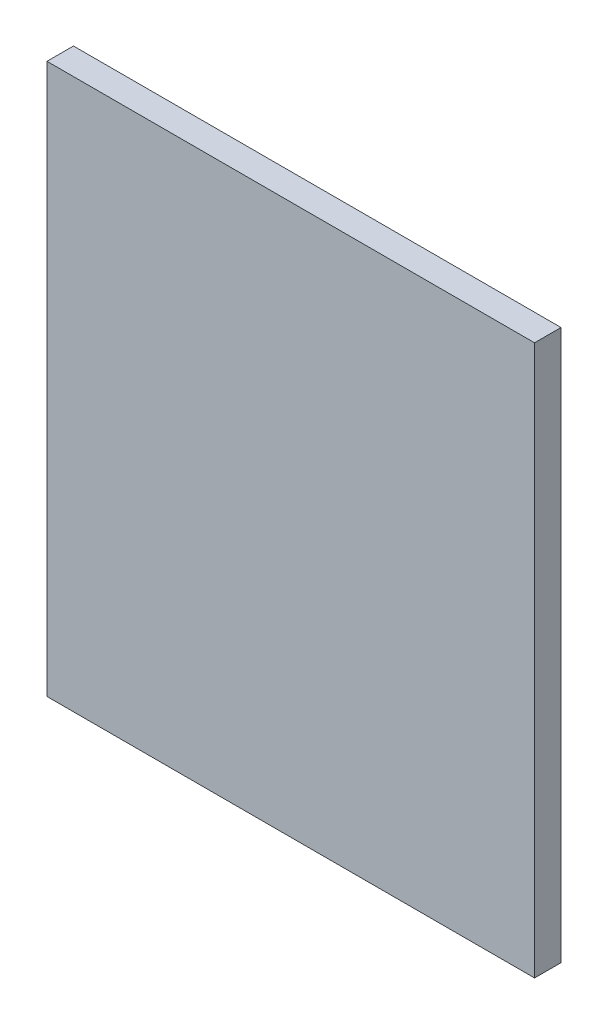
SolidWorks part; units mm, degrees
ref_plane "Alzado" through (0, 0, 0) normal (0, 0, 1) x (1, 0, 0)
ref_plane "Planta" through (0, 0, 0) normal (0, 1, 0) x (1, 0, 0)
ref_plane "Vista lateral" through (0, 0, 0) normal (1, 0, 0) x (0, 0, -1)
sketch "Croquis1" plane through (0, 0, 0) normal (0, 0, 1) x (1, 0, 0)
  line L1 (-813.2, 428.1119) -> (291.3533, 428.1119)
  line L2 (-813.2, 428.1119) -> (-813.2, -818.1181)
  line L3 (-813.2, -818.1181) -> (291.3533, -818.1181)
  line L4 (291.3533, 428.1119) -> (291.3533, -818.1181)
extrude "Saliente-Extruir1" add sketch "Croquis1" along normal blind 60
